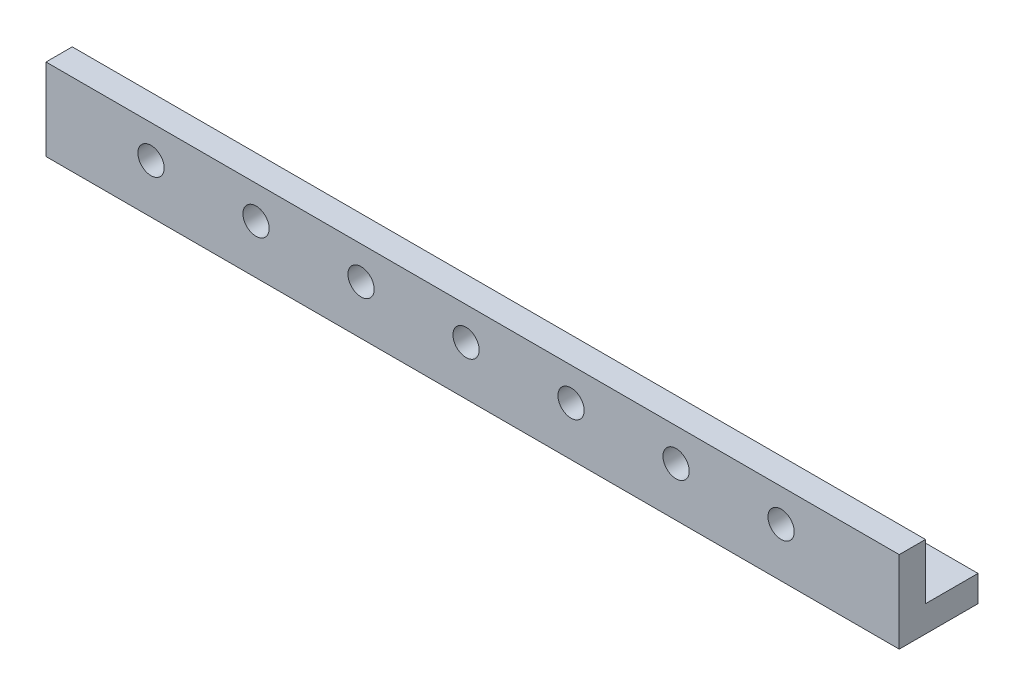
SolidWorks part; units mm, degrees
material "3003-O"
ref_plane "Front Plane" through (0, 0, 0) normal (0, 0, 1) x (1, 0, 0)
ref_plane "Top Plane" through (0, 0, 0) normal (0, 1, 0) x (1, 0, 0)
ref_plane "Right Plane" through (0, 0, 0) normal (1, 0, 0) x (0, 0, -1)
sketch "Sketch1" plane through (0, 0, 0) normal (1, 0, 0) x (0, 0, -1)
  line L0 (0, 0) -> (0, 19.812)
  line L1 (0, 19.812) -> (6.35, 19.812)
  line L2 (6.35, 19.812) -> (6.35, 6.35)
  line L3 (6.35, 6.35) -> (19.05, 6.35)
  line L4 (19.05, 6.35) -> (19.05, 0)
  line L5 (19.05, 0) -> (0, 0)
  dimension "D1" = 6.35
  dimension "D2" = 6.35
  dimension "D3" = 19.05
  dimension "D4" = 19.812
extrude "Boss-Extrude1" add sketch "Sketch1" along normal blind 206.375
sketch "Sketch2" plane through (0, 0, 0) normal (0, 0, 1) x (1, 0, 0)
  line L0 (206.375, 19.812) -> (0, 19.812) construction
  line L1 (0, 19.812) -> (0, 0) construction
  circle A0 centre (25.4, 11.8745) radius 3.175
  dimension "D1" = 6.35
  dimension "D2" = 7.9375
  dimension "D3" = 25.4
extrude "Cut-Extrude1" cut sketch "Sketch2" against normal through all contours A0
pattern_linear "LPattern1" count 7 spacing 25.4 along (1, 0, 0) of "Cut-Extrude1"
